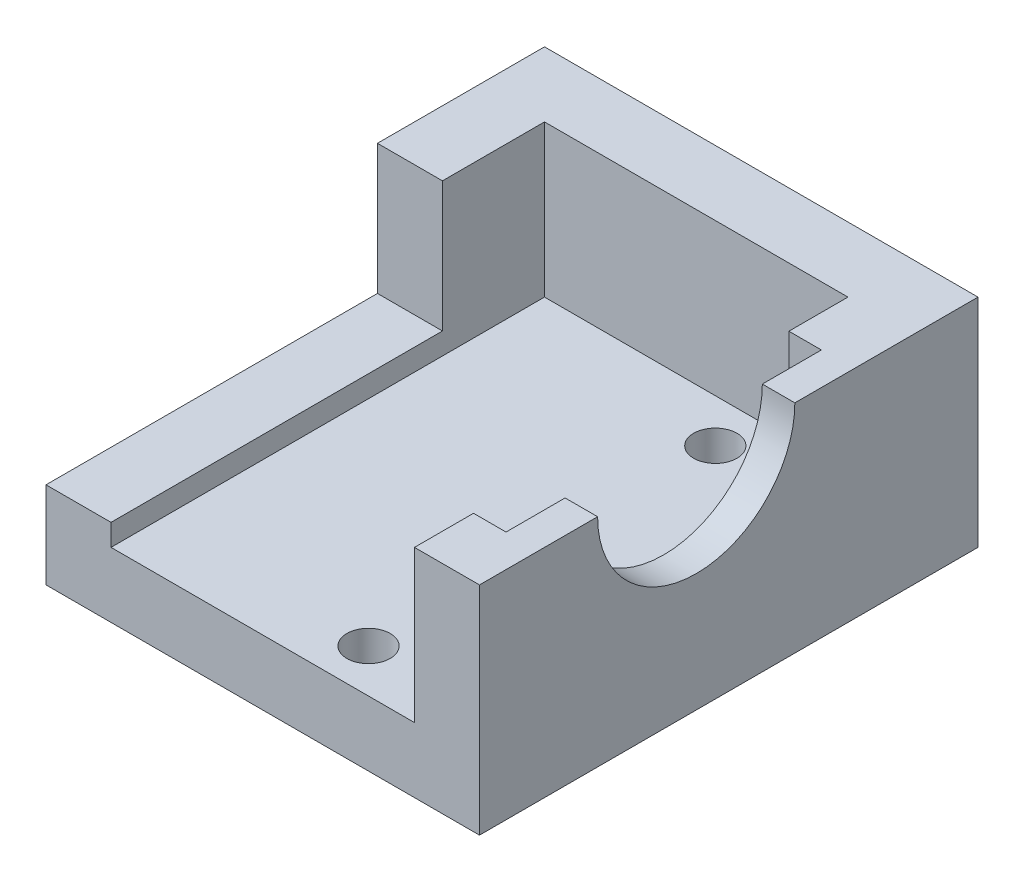
SolidWorks part; units mm, degrees
ref_plane "Front Plane" through (0, 0, 0) normal (0, 0, 1) x (1, 0, 0)
ref_plane "Top Plane" through (0, 0, 0) normal (0, 1, 0) x (1, 0, 0)
ref_plane "Right Plane" through (0, 0, 0) normal (1, 0, 0) x (0, 0, -1)
sketch "Sketch1" plane through (0, 0, 0) normal (0, 1, 0) x (1, 0, 0)
  line L1 (10, -11.5) -> (-10, -11.5)
  line L2 (10, -11.5) -> (10, 11.5)
  line L3 (10, 11.5) -> (-10, 11.5)
  line L4 (-10, -11.5) -> (-10, 11.5)
  line L5 (10, -11.5) -> (-10, 11.5) construction
  line L6 (10, 11.5) -> (-10, -11.5) construction
  point P0 (0, 0)
  dimension "D1" = 20
  dimension "D2" = 23
extrude "Boss-Extrude1" add sketch "Sketch1" along normal blind 10
sketch "Sketch3" plane through (0, 10, 0) normal (0, 1, 0) x (1, 0, 0)
  line L0 (0, -11.5) -> (-7, -11.5)
  line L1 (-10, -11.5) -> (10, -11.5) construction
  line L2 (0, -11.5) -> (7, -11.5)
  line L3 (-7, -11.5) -> (-7, 8.5)
  line L4 (-7, 8.5) -> (7, 8.5)
  line L5 (7, 8.5) -> (7, -11.5)
  dimension "D1" = 7
  dimension "D2" = 7
  dimension "D3" = 20
extrude "Cut-Extrude1" cut sketch "Sketch3" against normal blind 7
sketch "Sketch4" plane through (10, 0, 0) normal (1, 0, 0) x (0, 0, -1)
  line L0 (-11.5, 10) -> (-1.5, 10) construction
  line L3 (-11.5, 10) -> (11.5, 10) construction
  circle A1 centre (-1.5, 10) radius 4.55
  dimension "D1" = 10
  dimension "D2" = 9.1
extrude "Cut-Extrude6" cut sketch "Sketch4" against normal blind 7
sketch "Sketch9" plane through (7, 0, 0) normal (-1, 0, 0) x (0, 0, 1)
  line L0 (6.05, 10) -> (8.775, 10) construction
  line L1 (11.5, 10) -> (6.05, 10) construction
  line L2 (-3.05, 10) -> (-5.775, 10) construction
  line L3 (-3.05, 10) -> (-8.5, 10) construction
  line L4 (11.5, 3) -> (-8.5, 3) construction
  line L5 (-5.775, 10) -> (8.775, 10)
  line L6 (-5.775, 10) -> (-5.775, 3)
  line L7 (-5.775, 3) -> (8.775, 3)
  line L8 (8.775, 10) -> (8.775, 3)
extrude "Cut-Extrude8" cut sketch "Sketch9" against normal blind 1.5
sketch "Sketch10" plane through (-10, 0, 0) normal (-1, 0, 0) x (0, 0, 1)
  line L1 (11.5, 10) -> (-3.7914, 10)
  line L2 (11.5, 10) -> (11.5, 4)
  line L3 (11.5, 4) -> (-3.7914, 4)
  line L4 (-3.7914, 10) -> (-3.7914, 4)
  dimension "D1" = 6
extrude "Cut-Extrude9" cut sketch "Sketch10" against normal blind 5.5
sketch "Sketch11" plane through (0, 0, 0) normal (0, -1, 0) x (1, 0, 0)
  line L0 (10, 11.5) -> (2.88, 11.5) construction
  line L1 (-10, 11.5) -> (10, 11.5) construction
  line L2 (2.88, 11.5) -> (2.88, 9.5) construction
  line L3 (2.88, 9.5) -> (2.88, -6.5) construction
  circle A0 centre (2.88, 9.5) radius 1
  circle A1 centre (2.88, -6.5) radius 1
  dimension "D3" = 2
  dimension "D5" = 2
  dimension "D1" = 7.12
  dimension "D2" = 2
  dimension "D4" = 16
extrude "Cut-Extrude10" cut sketch "Sketch11" against normal blind 5.5
